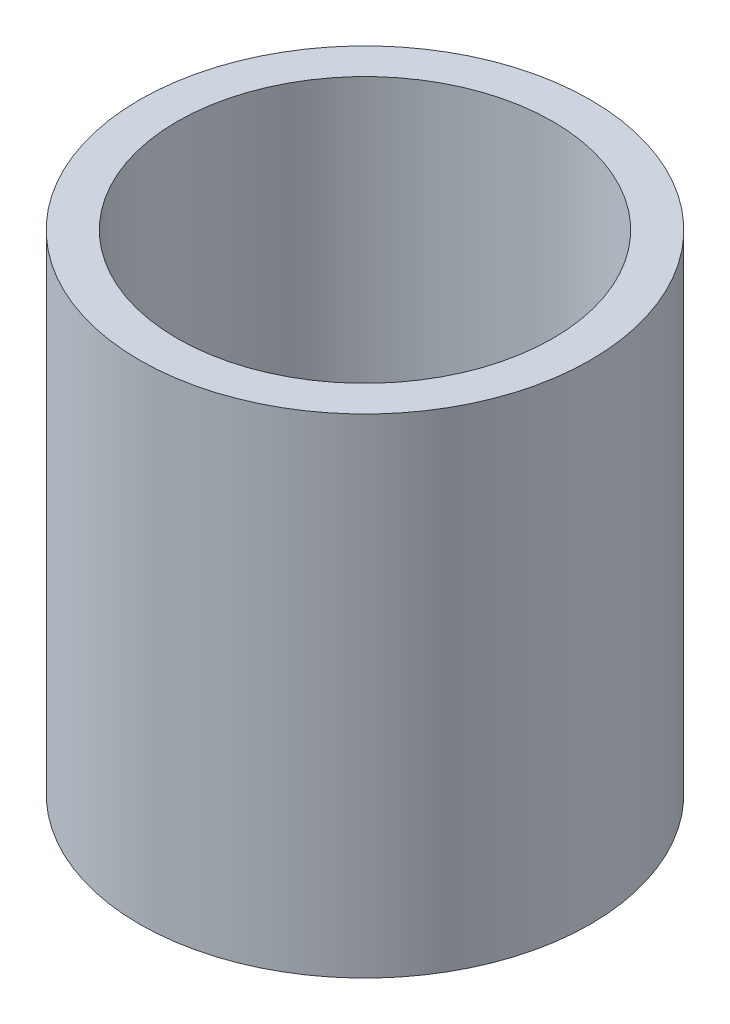
SolidWorks part; units mm, degrees
material "Custom Plastic"
ref_plane "X-Y Datum" through (0, 0, 0) normal (0, 0, 1) x (1, 0, 0)
ref_plane "X-Z Datum" through (0, 0, 0) normal (0, 1, 0) x (1, 0, 0)
ref_plane "Y-Z Datum" through (0, 0, 0) normal (1, 0, 0) x (0, 0, -1)
sketch "Sketch1" plane through (0, 0, 0) normal (0, 1, 0) x (1, 0, 0)
  circle A0 centre (0, 0) radius 3.9688
  circle A1 centre (0, 0) radius 4.7625
  dimension "D1" = 7.9375
  dimension "D2" = 9.525
extrude "Boss-Extrude1" add sketch "Sketch1" along normal blind 10.32
